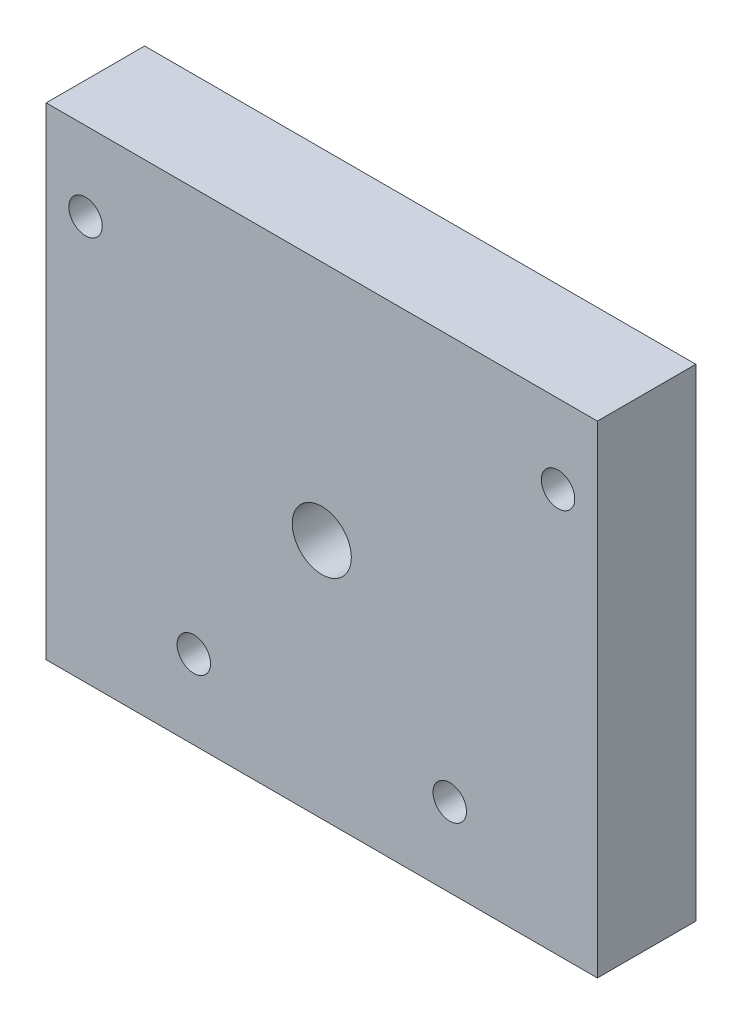
SolidWorks part; units mm, degrees
ref_plane "Front Plane" through (0, 0, 0) normal (0, 0, 1) x (1, 0, 0)
ref_plane "Top Plane" through (0, 0, 0) normal (0, 1, 0) x (1, 0, 0)
ref_plane "Right Plane" through (0, 0, 0) normal (1, 0, 0) x (0, 0, -1)
sketch "Sketch1" plane through (0, 0, 0) normal (0, 0, 1) x (1, 0, 0)
  line L2 (-140, -122.5) -> (-140, 122.5)
  line L3 (-140, 122.5) -> (140, 122.5)
  line L4 (140, -122.5) -> (140, 122.5)
  line L5 (-140, -122.5) -> (140, -122.5)
  circle A0 centre (0, 0) radius 15
  circle A6 centre (-120, 82.5) radius 5.25
  circle A7 centre (120, 82.5) radius 5.25
  circle A8 centre (-65, -82.5) radius 5.25
  circle A9 centre (65, -82.5) radius 5.25
  point P0 (0, 0)
  dimension "D1" = 2
  dimension "D2" = 2
extrude "Boss-Extrude1" add sketch "Sketch1" along normal blind 50
sketch "Sketch2" plane through (0, 0, 50) normal (0, 0, 1) x (1, 0, 0)
  circle A0 centre (-120, 82.5) radius 8.5
  circle A1 centre (120, 82.5) radius 8.5
  circle A2 centre (65, -82.5) radius 8.5
  circle A3 centre (-65, -82.5) radius 8.5
extrude "Cut-Extrude1" cut sketch "Sketch2" against normal blind 12
